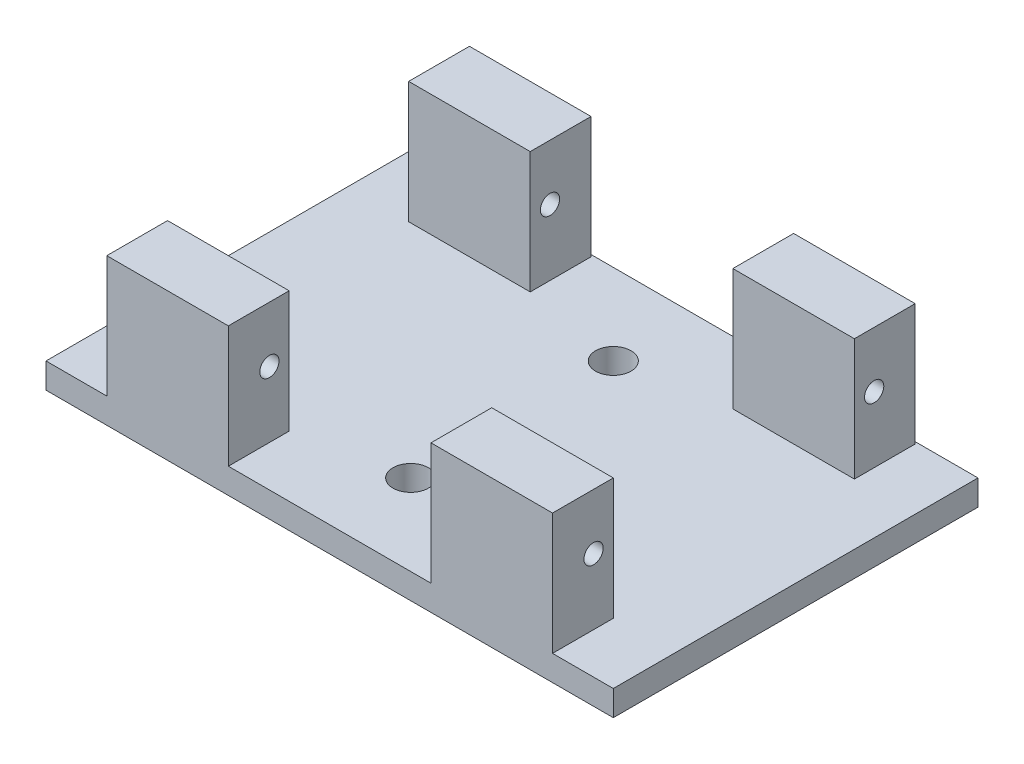
SolidWorks part; units mm, degrees
ref_plane "前视基准面" through (0, 0, 0) normal (0, 0, 1) x (1, 0, 0)
ref_plane "上视基准面" through (0, 0, 0) normal (0, 1, 0) x (1, 0, 0)
ref_plane "右视基准面" through (0, 0, 0) normal (1, 0, 0) x (0, 0, -1)
other "Configuration Table"
sketch "草图1" plane through (0, 0, 0) normal (0, 1, 0) x (1, 0, 0)
  line L1 (-28, 18) -> (28, 18)
  line L2 (-28, 18) -> (-28, -18)
  line L3 (-28, -18) -> (28, -18)
  line L4 (28, 18) -> (28, -18)
  line L5 (-28, 18) -> (28, -18) construction
  line L6 (-28, -18) -> (28, 18) construction
  point P0 (0, 0)
  dimension "D1" = 56
  dimension "D2" = 36
extrude "凸台-拉伸1" add sketch "草图1" along normal blind 2.5
sketch "草图2" plane through (0, 2.5, 0) normal (0, 1, 0) x (1, 0, 0)
  line L0 (-28, -18) -> (28, -18) construction
  line L1 (10, 17.8) -> (22, 17.8)
  line L2 (10, 17.8) -> (10, 11.8)
  line L3 (10, 11.8) -> (22, 11.8)
  line L4 (22, 17.8) -> (22, 11.8)
  line L5 (10, -12) -> (22, -12)
  line L6 (10, -12) -> (10, -18)
  line L7 (10, -18) -> (22, -18)
  line L8 (22, -12) -> (22, -18)
  line L9 (28, -18) -> (28, 18) construction
  dimension "D1" = 23.8
  dimension "D2" = 6
  dimension "D3" = 6
  dimension "D4" = 12
  dimension "D5" = 6
extrude "凸台-拉伸2" add sketch "草图2" along normal blind 12
sketch "草图3" plane through (22, 0, 0) normal (1, 0, 0) x (0, 0, -1)
  line L0 (-18, 2.5) -> (18, 2.5) construction
  line L1 (11.8, 2.5) -> (17.8, 2.5) construction
  line L2 (-12, 14.5) -> (-12, 2.5) construction
  line L3 (11.8, 14.5) -> (11.8, 2.5) construction
  circle A0 centre (-13.95, 9) radius 0.95
  circle A1 centre (13.75, 9) radius 0.95
  dimension "D1" = 6.5
  dimension "D2" = 6.5
  dimension "D3" = 1.95
  dimension "D4" = 1.95
  dimension "D5" = 1.9
  dimension "D6" = 1.9
extrude "切除-拉伸1" cut sketch "草图3" against normal through all
mirror "镜向1" about plane through (0, 0, 0) normal (1, 0, 0) of "切除-拉伸1", "凸台-拉伸2"
sketch "草图4" plane through (0, 2.5, 0) normal (0, 1, 0) x (1, 0, 0)
  circle A0 centre (0, -10) radius 1.75
  circle A1 centre (0, 10) radius 1.75
  dimension "D1" = 20
  dimension "D2" = 3.5
  dimension "D3" = 3.5
  dimension "D4" = 10
extrude "切除-拉伸2" cut sketch "草图4" against normal through all
